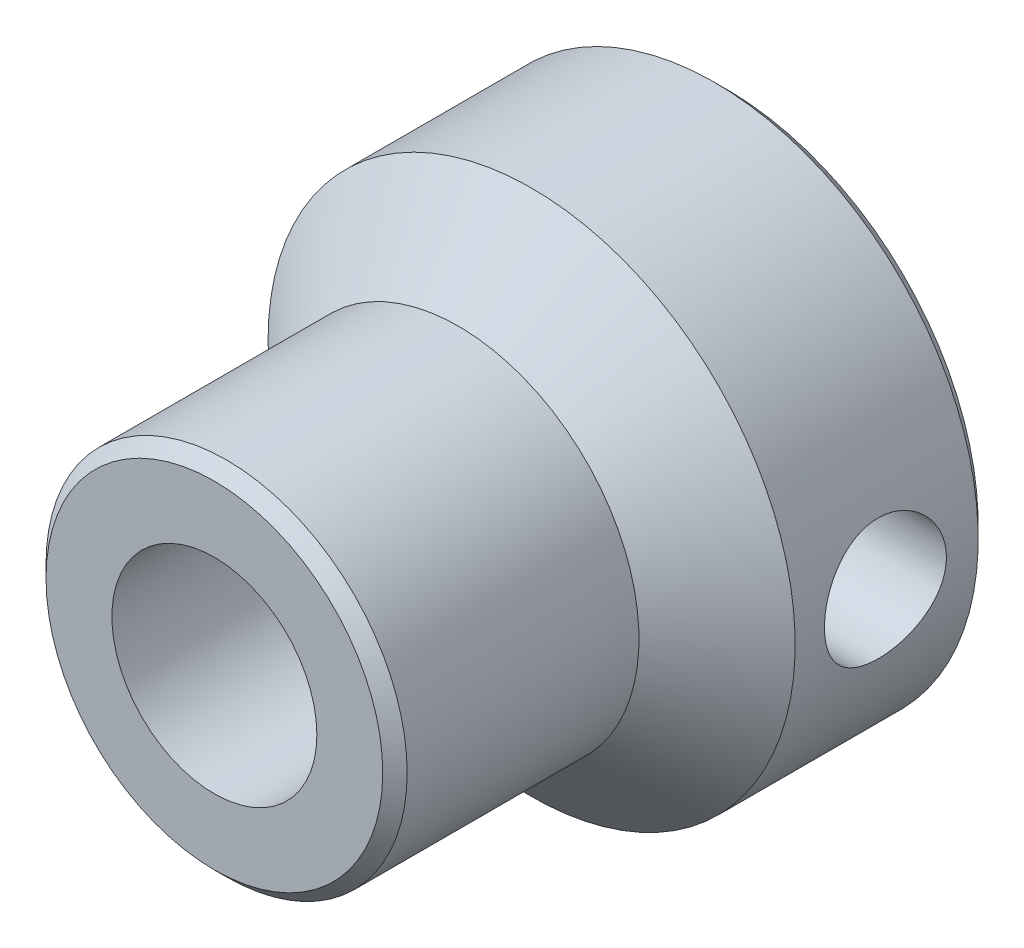
SolidWorks part; units mm, degrees
ref_plane "Top" through (0, 0, 0) normal (0, 0, 1) x (1, 0, 0)
ref_plane "Front" through (0, 0, 0) normal (0, 1, 0) x (1, 0, 0)
ref_plane "Right" through (0, 0, 0) normal (1, 0, 0) x (0, 0, -1)
ref_plane "Base Tangent Plane" through (5.4, 0, 0) normal (1, 0, 0) x (0, 0, -1)
sketch "Body Sketch" plane through (0, 0, 0) normal (0, 1, 0) x (-1, 0, 0)
  line L1 (1, 10.5) -> (3.7, 10.5)
  line L2 (3.7, 10.5) -> (3.7, 5.5)
  line L3 (3.7, 5.5) -> (5.4, 4)
  line L4 (5.4, 4) -> (5.4, 0)
  line L5 (5.4, 0) -> (2.5, 0)
  line L8 (0, 0) -> (0, 10.5) construction
  line L9 (1, 10.5) -> (1, 5)
  line L10 (1, 5) -> (2.5, 5)
  line L11 (2.5, 5) -> (2.5, 0)
  dimension "D1" = 4
  dimension "D6" = 5
  dimension "D2" = 10.5
  dimension "D4" = 5.4
  dimension "D3" = 3.7
  dimension "D5" = 2.5
  dimension "D7" = 1
  dimension "D8" = 5
revolve "Body Revolve" add sketch "Body Sketch" angle 360 about L8
hole_wizard "Connector M5x0.8 Tapped Hole" positions "Connector Position Sketch" profile "Sketch5" tap size "M5x0.8" standard "ANSI Metric" end condition through all
sketch "Connector Position Sketch" plane through (0, 0, 10.5) normal (0, 0, 1) x (1, 0, 0)
  point P0 (0, 0)
cosmetic thread "Connector Hole Thread"
sketch "Sketch5" plane through (0, 0, 10.5) normal (1, 0, 0) x (0, -1, 0)
  line L0 (0, 0) -> (0, 10.5)
  line L1 (0, 10.5) -> (2.1, 10.5)
  line L2 (2.1, 10.5) -> (2.1, 0)
  line L5 (2.1, 0) -> (0, 0)
  line L11 (0, -6.35) -> (0, 107.95) construction
  dimension "Thru Tap Drill Dia." = 4.2
  dimension "Thru Tap Drill Depth" = 10.5
hole_wizard "Set Screw 1 M3x0.5 Tapped Hole" positions "Set Screw Position Sketch" profile "Set Screw Profile Sketch" tap size "M3x0.5" standard "ANSI Metric"
sketch3d "Set Screw Position Sketch"
  point P0 (5.4, 0, 2.15)
  dimension "D1" = 2.15
sketch "Set Screw Profile Sketch" plane through (5.4, 0, 2.15) normal (0, 1, 0) x (0, 0, -1)
  line L0 (0, 0) -> (0, 2.9)
  line L1 (0, 2.9) -> (1.25, 2.9)
  line L2 (1.25, 2.9) -> (1.25, 0)
  line L5 (1.25, 0) -> (0, 0)
  line L11 (0, -6.35) -> (0, 107.95) construction
  dimension "Thru Tap Drill Dia." = 2.5
  dimension "Thru Tap Drill Depth" = 2.9
cosmetic thread "Set Screw 1 Hole Thread"
pattern_circular "Set Screw 2 Pattern" count 2 over 360 about axis through (0, 0, 2.15) along (1, 0, 0) of "Set Screw 1 M3x0.5 Tapped Hole"
cosmetic thread "Hole Thread3"
chamfer "Edge Chamfers" distance 0.25 angle 45 2 edges at (-5.4, 0, 0) (-3.7, 0, 10.5)
equation "\"Base Diameter\"= 10.8"
equation "\"D4@Body Sketch\"=\"Base Diameter\"/2"
equation "\"D1@Base Tangent Plane\"=\"Base Diameter\"/2"
